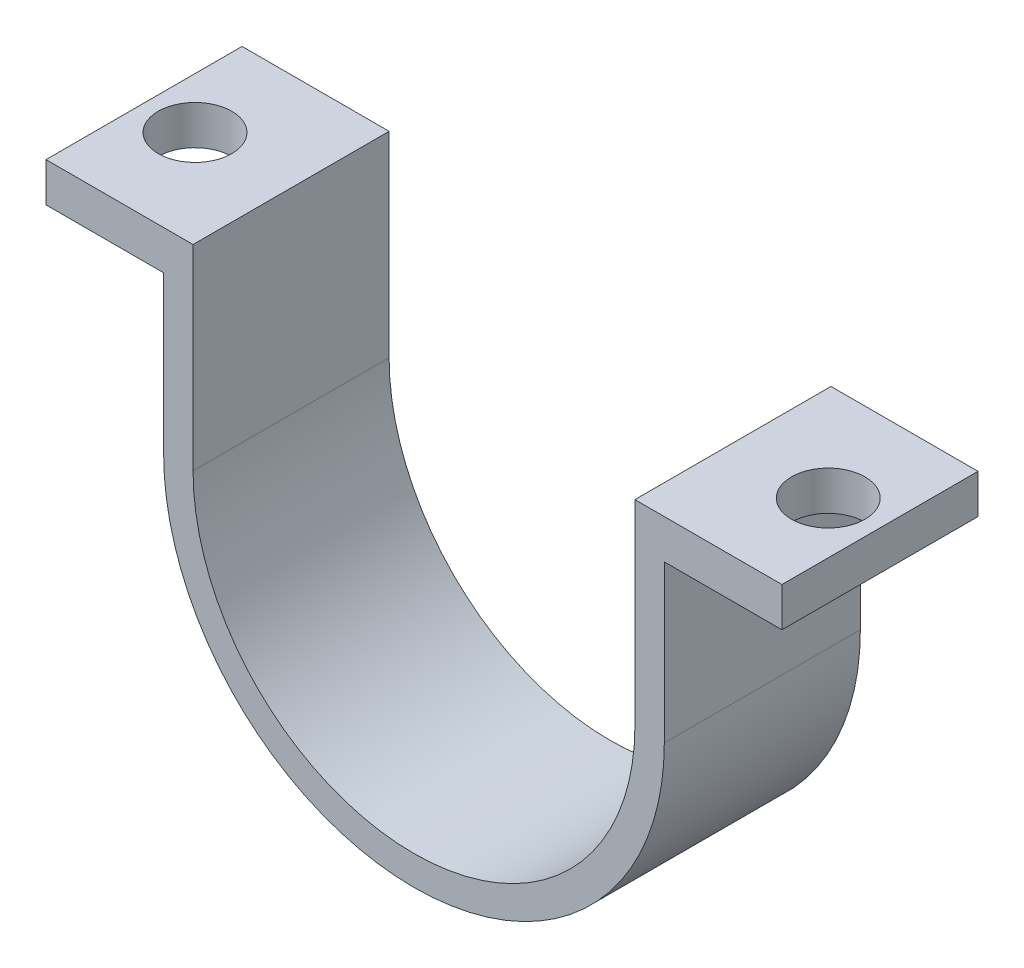
SolidWorks part; units mm, degrees
material "7075-T6, Plate (SS)"
ref_plane "Front Plane" through (0, 0, 0) normal (0, 0, 1) x (1, 0, 0)
ref_plane "Top Plane" through (0, 0, 0) normal (0, 1, 0) x (1, 0, 0)
ref_plane "Right Plane" through (0, 0, 0) normal (1, 0, 0) x (0, 0, -1)
sketch "Sketch4" plane through (0, 0, 0) normal (0, 0, 1) x (1, 0, 0)
  line L0 (-32.385, 15.24) -> (-47.625, 15.24)
  line L1 (-47.625, 15.24) -> (-47.625, 20.32)
  line L2 (-47.625, 20.32) -> (-28.575, 20.32)
  line L3 (-28.575, 20.32) -> (-28.575, -5.08)
  line L4 (-32.385, -5.08) -> (-32.385, 15.24)
  line L5 (32.4814, -5.08) -> (32.4814, 15.24)
  line L6 (32.4814, 15.24) -> (47.7214, 15.24)
  line L7 (47.7214, 15.24) -> (47.7214, 20.32)
  line L8 (47.7214, 20.32) -> (28.6714, 20.32)
  line L9 (28.6714, 20.32) -> (28.6714, -5.08)
  arc A1 (32.4814, -5.08) -> (-32.385, -5.08) centre (0.0482, -5.08) cw
  arc A2 (-28.575, -5.08) -> (28.6714, -5.08) centre (0.0482, -5.08) ccw
  dimension "D10" = 20.32
  dimension "D11" = 20.32
  dimension "D12" = 32.4332
  dimension "D3" = 0
  dimension "D2" = 90
  dimension "D4" = 5.08
  dimension "D5" = 15.24
  dimension "D6" = 19.05
  dimension "D7" = 15.24
  dimension "D8" = 19.05
  dimension "D9" = 5.08
extrude "Boss-Extrude2" add sketch "Sketch4" along normal blind 25.4
sketch "Sketch5" plane through (0, 20.32, 0) normal (0, 1, 0) x (1, 0, 0)
  line L3 (-28.575, 0) -> (-47.625, 0) construction
  line L4 (47.7214, 0) -> (28.6714, 0) construction
  circle A0 centre (-41.021, -12.7) radius 4.7625
  circle A1 centre (41.021, -12.7) radius 4.7625
  dimension "D1" = 82.042
  dimension "D2" = 41.021
  dimension "D3" = 9.525
  dimension "D4" = 9.525
  dimension "D5" = 12.7
  dimension "D6" = 12.7
extrude "Cut-Extrude1" cut sketch "Sketch5" against normal blind 38.1
